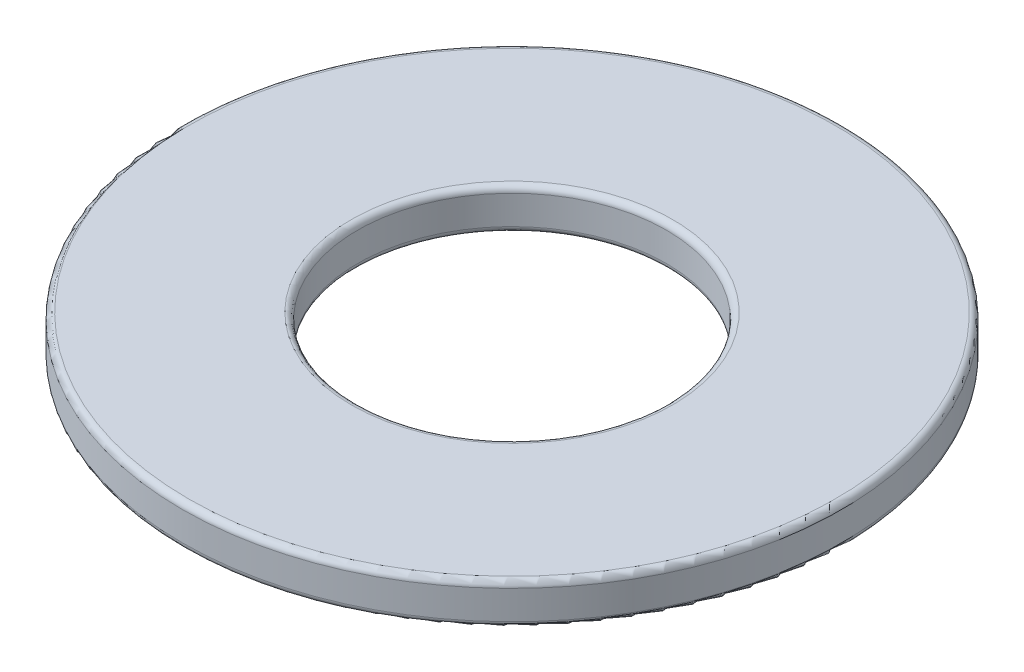
SolidWorks part; units mm, degrees
ref_plane "Front Plane" through (0, 0, 0) normal (0, 0, 1) x (1, 0, 0)
ref_plane "Top Plane" through (0, 0, 0) normal (0, 1, 0) x (1, 0, 0)
ref_plane "Right Plane" through (0, 0, 0) normal (1, 0, 0) x (0, 0, -1)
sketch "Sketch1" plane through (0, 0, 0) normal (0, 1, 0) x (1, 0, 0)
  circle A0 centre (0, 0) radius 3.75
  circle A1 centre (0, 0) radius 8
  dimension "D1" = 7.5
  dimension "D2" = 16
extrude "Boss-Extrude1" add sketch "Sketch1" along normal mid plane 1
fillet "Fillet1" radius 0.15 4 edges at (0, -0.5, 3.75) (0, 0.5, 3.75) (0, -0.5, 8) (0, 0.5, 8)
